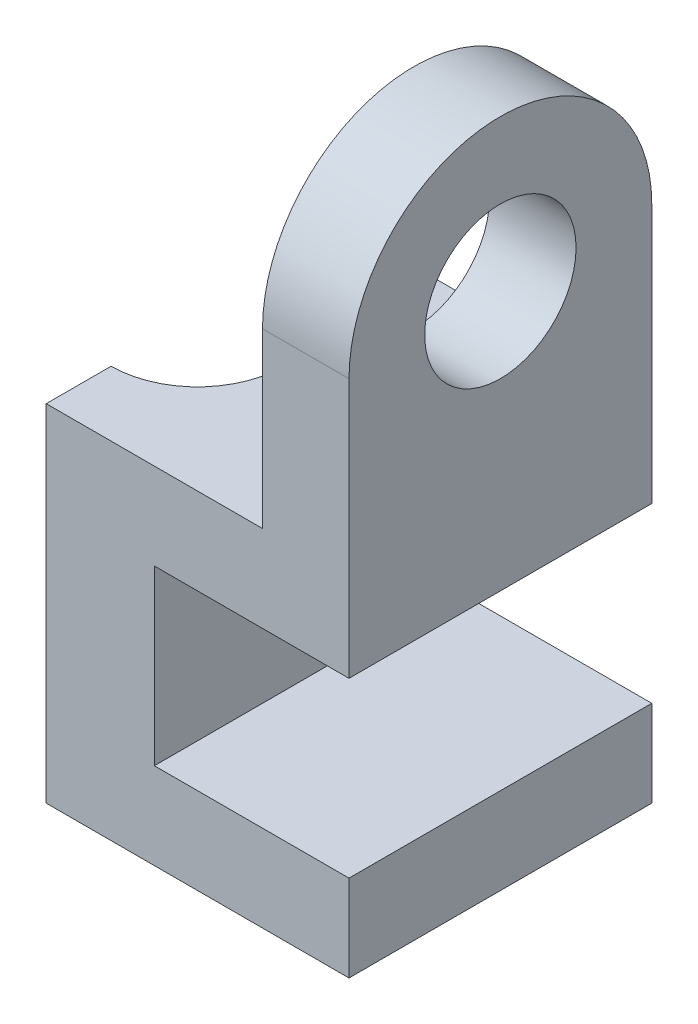
SolidWorks part; units mm, degrees
ref_plane "Front Plane" through (0, 0, 0) normal (0, 0, 1) x (1, 0, 0)
ref_plane "Top Plane" through (0, 0, 0) normal (0, 1, 0) x (1, 0, 0)
ref_plane "Right Plane" through (0, 0, 0) normal (1, 0, 0) x (0, 0, -1)
sketch "Sketch1" plane through (0, 0, 0) normal (0, 0, 1) x (1, 0, 0)
  line L1 (-35, 40) -> (35, 40)
  line L2 (-35, 40) -> (-35, -40)
  line L3 (-35, -40) -> (35, -40)
  line L4 (35, 40) -> (35, -40)
  line L5 (-35, 40) -> (35, -40) construction
  line L6 (-35, -40) -> (35, 40) construction
  point P0 (0, 0)
  dimension "D1" = 70
  dimension "D2" = 80
extrude "Boss-Extrude1" add sketch "Sketch1" along normal blind 70
sketch "Sketch2" plane through (0, 0, 70) normal (0, 0, 1) x (1, 0, 0)
  line L0 (35, -40) -> (35, 40) construction
  line L1 (35, -20) -> (-10, -20)
  line L2 (35, -20) -> (35, 20)
  line L3 (35, 20) -> (-10, 20)
  line L4 (-10, -20) -> (-10, 20)
  line L5 (35, 40) -> (-35, 40) construction
  line L6 (-35, -40) -> (35, -40) construction
  dimension "D1" = 20
  dimension "D2" = 20
  dimension "D3" = 45
extrude "Cut-Extrude1" cut sketch "Sketch2" against normal blind 70
sketch "Sketch3" plane through (0, 40, 0) normal (0, 1, 0) x (1, 0, 0)
  line L0 (0, 0) -> (0, -70) construction
  line L1 (35, -70) -> (-35, -70) construction
  line L2 (-35, -35) -> (35, -35) construction
  line L3 (-35, -70) -> (-35, 0) construction
  line L4 (35, -70) -> (35, 0) construction
  line L5 (-35, -55) -> (-35, -15)
  arc A0 (-35, -55) -> (-35, -15) centre (-35, -35) ccw
  dimension "D1" = 40
extrude "Cut-Extrude2" cut sketch "Sketch3" against normal through all both and the other way through all
ref_plane "Plane1" through (35, 0, 0) normal (1, 0, 0) x (0, 0, -1)
sketch "Sketch4" plane through (35, 0, 0) normal (1, 0, 0) x (0, 0, -1)
  line L0 (-70, 40) -> (-70, 80)
  line L1 (0, 80) -> (0, 40)
  line L2 (-70, 40) -> (0, 40) construction
  line L3 (-70, 40) -> (0, 40)
  arc A0 (-70, 80) -> (0, 80) centre (-35, 80) cw
  dimension "D1" = 120
extrude "Boss-Extrude2" add sketch "Sketch4" against normal blind 20
sketch "Sketch5" plane through (35, 0, 0) normal (1, 0, 0) x (0, 0, -1)
  line L0 (-70, 80) -> (0, 80) construction
  circle A0 centre (-35, 80) radius 17.5
  dimension "D1" = 35
extrude "Cut-Extrude3" cut sketch "Sketch5" against normal blind 20
